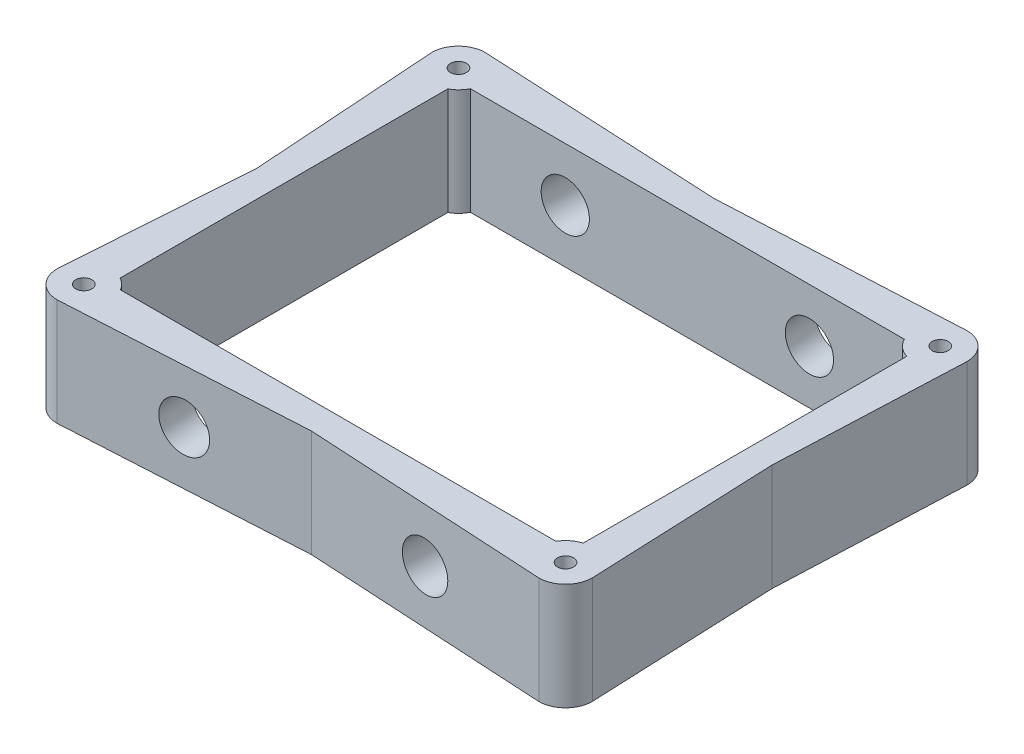
SolidWorks part; units mm, degrees
ref_plane "Front Plane" through (0, 0, 0) normal (0, 0, 1) x (1, 0, 0)
ref_plane "Top Plane" through (0, 0, 0) normal (0, 1, 0) x (1, 0, 0)
ref_plane "Right Plane" through (0, 0, 0) normal (1, 0, 0) x (0, 0, -1)
other "Center of Mass"
sketch "Sketch1" plane through (0, 0, 0) normal (0, 1, 0) x (1, 0, 0)
  line L0 (-45, 40) -> (0, 37.7582)
  line L1 (-40.6853, -32.4735) -> (40.6853, -32.4735)
  line L2 (-42.6109, -30.6077) -> (-42.6109, 30.6077)
  line L3 (-40.5307, 32.7582) -> (40.5307, 32.7582)
  line L4 (43.5292, -30.2212) -> (43.5292, 30.2212)
  line L5 (-45, -35) -> (45, 35) construction
  line L6 (-45, 35) -> (45, -35) construction
  line L7 (-50, 35) -> (-47.6109, 0)
  line L8 (-50, -35) -> (-47.6109, 0)
  line L9 (-45, -40) -> (0, -37.4735)
  line L10 (0, -37.4735) -> (45, -40)
  line L11 (50, -35) -> (48.5292, 0)
  line L12 (48.5292, 0) -> (50, 35)
  line L14 (45, 40) -> (0, 37.7582)
  arc A0 (-42.6109, 30.6077) -> (-40.5307, 32.7582) centre (-45, 35) ccw
  arc A1 (40.5307, 32.7582) -> (43.5292, 30.2212) centre (45, 35) ccw
  arc A2 (-40.6853, -32.4735) -> (-42.6109, -30.6077) centre (-45, -35) ccw
  arc A3 (45, -40) -> (49.9824, -34.5805) centre (45, -35) ccw
  arc A4 (-44.5031, 39.9752) -> (-49.9536, 34.3206) centre (-45, 35) ccw
  arc A5 (49.9824, 34.5805) -> (44.5031, 39.9752) centre (45, 35) ccw
  arc A6 (43.5292, -30.2212) -> (40.6853, -32.4735) centre (45, -35) ccw
  arc A7 (-49.9536, -34.3206) -> (-45, -40) centre (-45, -35) ccw
  circle A8 centre (45, 35) radius 1.5
  circle A9 centre (45, -35) radius 1.5
  circle A10 centre (-45, -35) radius 1.5
  circle A11 centre (-45, 35) radius 1.5
  point P0 (0, 0)
  point P31 (45, -35)
  point P34 (45, 35)
  point P35 (-45, 35)
  point P36 (-45, -35)
  dimension "D3" = 10
  dimension "D4" = 10
  dimension "D5" = 10
  dimension "D6" = 10
  dimension "D11" = 3
  dimension "D12" = 3
  dimension "D13" = 3
  dimension "D14" = 3
  dimension "D1" = 90
  dimension "D2" = 70
  dimension "D7" = 5
  dimension "D8" = 5
  dimension "D9" = 5
  dimension "D10" = 5
extrude "Boss-Extrude3" add sketch "Sketch1" along normal blind 20 contours L8 A7 L9 L10 A3 L11 L12 A5 L14 L0 A4 L7 A11 A10 A9 A8 L4 A6 L1 A2 L2 A0 L3 A1
hole_wizard "M10x1.0 Tapped Hole2" positions "Sketch16" profile "Sketch15" tap size "M10x1.0" standard "ANSI Metric"
sketch "Sketch16" plane through (2.0973, 0, 37.3558) normal (0.0561, 0, 0.9984) x (0.9984, 0, -0.0561)
  line L0 (-47.1715, 20) -> (-2.1006, 20) construction
  line L1 (-24.6361, 20) -> (-24.6361, 0)
  line L2 (-47.1715, 0) -> (-2.1006, 0) construction
  point P12 (-24.6361, 10)
sketch "Sketch15" plane through (-22.5, 10, 38.7368) normal (0, 1, 0) x (0.9984, 0, -0.0561)
  line L0 (0, 0) -> (0, 6.2731)
  line L1 (0, 6.2731) -> (4.5, 6.2731)
  line L2 (4.5, 6.2731) -> (4.5, 0)
  line L5 (4.5, 0) -> (0, 0)
  line L11 (0, -6.35) -> (0, 107.95) construction
  dimension "Thru Tap Drill Dia." = 9
  dimension "Thru Tap Drill Depth" = 6.2731
cosmetic thread "Hole Thread16" parameters "D2"=10
hole_wizard "M10x1.0 Tapped Hole3" positions "Sketch20" profile "Sketch19" tap size "M10x1.0" standard "ANSI Metric"
sketch "Sketch20" plane through (-2.0973, 0, 37.3558) normal (-0.0561, 0, 0.9984) x (0.9984, 0, 0.0561)
  line L0 (24.6361, 20) -> (24.6361, 0)
  line L1 (2.1006, 20) -> (47.1715, 20) construction
  line L2 (2.1006, 0) -> (47.1715, 0) construction
  point P9 (24.6361, 10)
sketch "Sketch19" plane through (22.5, 10, 38.7368) normal (0, 1, 0) x (0.9984, 0, 0.0561)
  line L0 (0, 0) -> (0, 6.2731)
  line L1 (0, 6.2731) -> (4.5, 6.2731)
  line L2 (4.5, 6.2731) -> (4.5, 0)
  line L5 (4.5, 0) -> (0, 0)
  line L11 (0, -6.35) -> (0, 107.95) construction
  dimension "Thru Tap Drill Dia." = 9
  dimension "Thru Tap Drill Depth" = 6.2731
cosmetic thread "Hole Thread17" parameters "D2"=10
hole_wizard "M10x1.0 Tapped Hole4" positions "Sketch23" profile "Sketch22" tap size "M10x1.0" standard "ANSI Metric"
sketch "Sketch23" plane through (-1.8764, 0, -37.6647) normal (-0.0498, 0, -0.9988) x (-0.9988, 0, 0.0498)
  line L0 (-24.4066, 20) -> (-24.4066, 0)
  line L1 (-46.9345, 20) -> (-1.8787, 20) construction
  line L2 (-46.9345, 0) -> (-1.8787, 0) construction
  point P9 (-24.4066, 10)
sketch "Sketch22" plane through (22.5, 10, -38.8791) normal (0, 1, 0) x (-0.9988, 0, 0.0498)
  line L0 (0, 0) -> (0, 6.1285)
  line L1 (0, 6.1285) -> (4.5, 6.1285)
  line L2 (4.5, 6.1285) -> (4.5, 0)
  line L5 (4.5, 0) -> (0, 0)
  line L11 (0, -6.35) -> (0, 107.95) construction
  dimension "Thru Tap Drill Dia." = 9
  dimension "Thru Tap Drill Depth" = 6.1285
cosmetic thread "Hole Thread18" parameters "D2"=10
hole_wizard "M10x1.0 Tapped Hole5" positions "Sketch26" profile "Sketch25" tap size "M10x1.0" standard "ANSI Metric"
sketch "Sketch26" plane through (1.8764, 0, -37.6647) normal (0.0498, 0, -0.9988) x (-0.9988, 0, -0.0498)
  line L0 (24.4066, 20) -> (24.4066, 0)
  line L1 (46.9345, 20) -> (1.8787, 20) construction
  line L2 (46.9345, 0) -> (1.8787, 0) construction
  point P9 (24.4066, 10)
sketch "Sketch25" plane through (-22.5, 10, -38.8791) normal (0, 1, 0) x (-0.9988, 0, -0.0498)
  line L0 (0, 0) -> (0, 6.1285)
  line L1 (0, 6.1285) -> (4.5, 6.1285)
  line L2 (4.5, 6.1285) -> (4.5, 0)
  line L5 (4.5, 0) -> (0, 0)
  line L11 (0, -6.35) -> (0, 107.95) construction
  dimension "Thru Tap Drill Dia." = 9
  dimension "Thru Tap Drill Depth" = 6.1285
cosmetic thread "Hole Thread19" parameters "D2"=10
